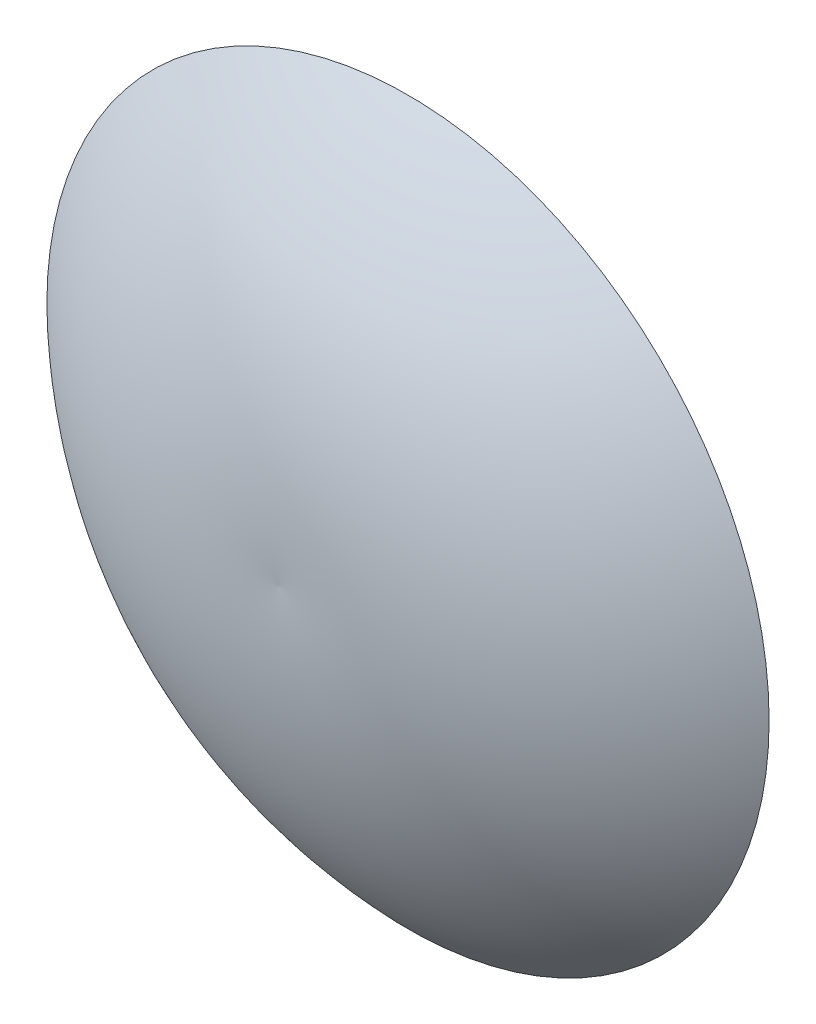
SolidWorks part; units mm, degrees
ref_plane "Front Plane" through (0, 0, 0) normal (0, 0, 1) x (1, 0, 0)
ref_plane "Top Plane" through (0, 0, 0) normal (0, 1, 0) x (1, 0, 0)
ref_plane "Right Plane" through (0, 0, 0) normal (1, 0, 0) x (0, 0, -1)
sketch "Sketch1" plane through (-1746.8311, 24.8451, -69.2951) normal (1, 0, 0) x (0, 0, -1)
  line L0 (-4692.501, -1194.5197) -> (-3960.5108, -1194.5197)
  line L1 (-3960.5108, -1194.5197) -> (-3960.5108, 857.1596)
  arc A0 (-3960.5108, 857.1596) -> (-4692.501, -1194.5197) centre (-1983.6965, -1004.5386) ccw
revolve "Revolve1" add sketch "Sketch1" angle 360 about L0
